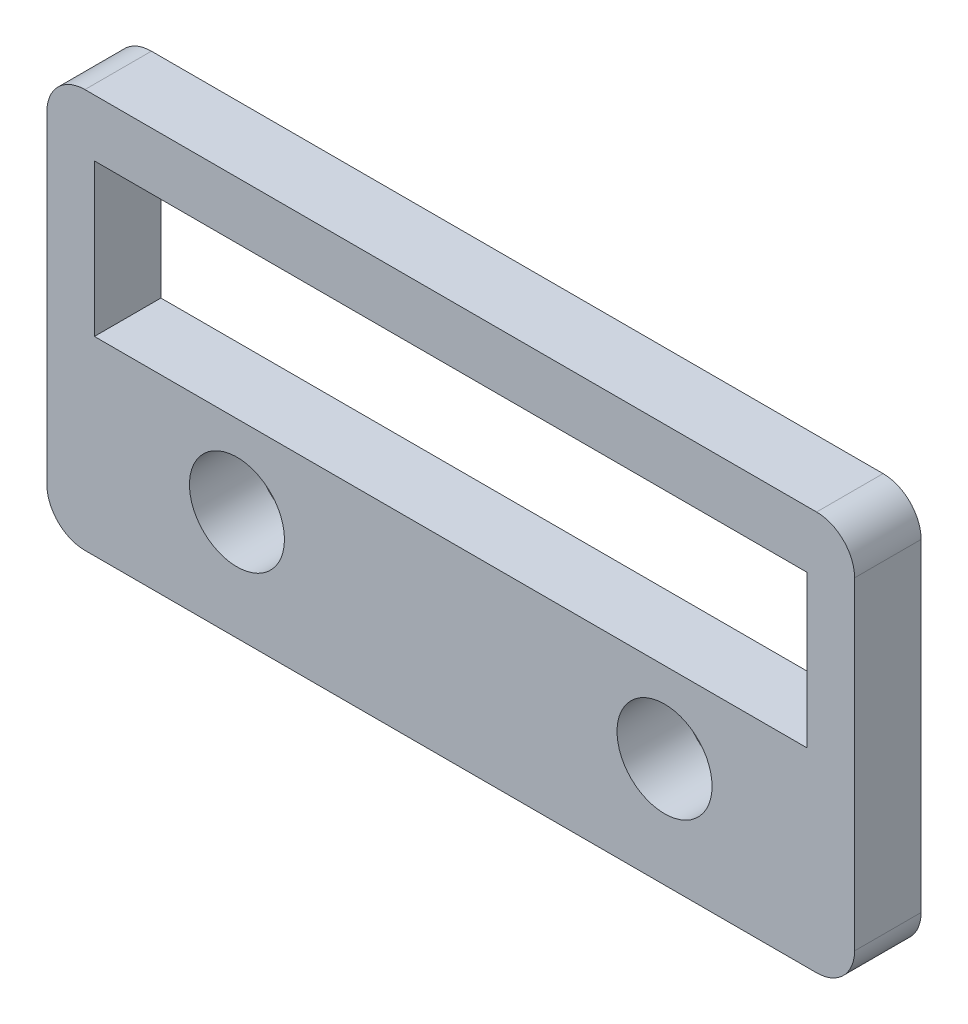
SolidWorks part; units mm, degrees
ref_plane "Front Plane" through (0, 0, 0) normal (0, 0, 1) x (1, 0, 0)
ref_plane "Top Plane" through (0, 0, 0) normal (0, 1, 0) x (1, 0, 0)
ref_plane "Right Plane" through (0, 0, 0) normal (1, 0, 0) x (0, 0, -1)
sketch "Sketch1" plane through (0, 0, 0) normal (0, 0, 1) x (1, 0, 0)
  line L1 (-29.3041, 27.5877) -> (47.6959, 27.5877)
  line L2 (-33.3041, 23.5877) -> (-33.3041, -10.4123)
  line L3 (-29.3041, -14.4123) -> (47.6959, -14.4123)
  line L4 (51.6959, 23.5877) -> (51.6959, -10.4123)
  arc A0 (47.6959, 27.5877) -> (51.6959, 23.5877) centre (47.6959, 23.5877) cw
  arc A1 (51.6959, -10.4123) -> (47.6959, -14.4123) centre (47.6959, -10.4123) cw
  arc A2 (-33.3041, -10.4123) -> (-29.3041, -14.4123) centre (-29.3041, -10.4123) ccw
  arc A3 (-33.3041, 23.5877) -> (-29.3041, 27.5877) centre (-29.3041, 23.5877) cw
  point P7 (51.6959, 27.5877)
  point P12 (-33.3041, -14.4123)
  point P15 (-33.3041, 27.5877)
  dimension "D4" = 4
  dimension "D1" = 85
  dimension "D2" = 42
  dimension "D3" = 33.3041
extrude "Boss-Extrude1" add sketch "Sketch1" along normal blind 7
sketch "Sketch2" plane through (0, 0, 7) normal (0, 0, 1) x (1, 0, 0)
  line L1 (-28.3041, 21.5877) -> (46.6959, 21.5877)
  line L2 (-28.3041, 21.5877) -> (-28.3041, 5.5877)
  line L3 (-28.3041, 5.5877) -> (46.6959, 5.5877)
  line L4 (46.6959, 21.5877) -> (46.6959, 5.5877)
  line L6 (47.6959, 27.5877) -> (-29.3041, 27.5877) construction
  line L7 (-33.3041, 23.5877) -> (-33.3041, -10.4123) construction
  dimension "D1" = 75
  dimension "D2" = 5
  dimension "D3" = 6
  dimension "D4" = 16
extrude "Cut-Extrude1" cut sketch "Sketch2" against normal blind 7
sketch "Sketch3" plane through (0, 0, 7) normal (0, 0, 1) x (1, 0, 0)
  line L0 (51.6959, -10.4123) -> (51.6959, 23.5877) construction
  line L1 (-29.3041, -14.4123) -> (47.6959, -14.4123) construction
  line L2 (-33.3041, 23.5877) -> (-33.3041, -10.4123) construction
  circle A0 centre (31.6959, -2.9123) radius 5
  circle A1 centre (-13.3041, -2.9123) radius 5
  dimension "D5" = 10
  dimension "D6" = 10
  dimension "D1" = 20
  dimension "D2" = 11.5
  dimension "D3" = 20
  dimension "D4" = 11.5
extrude "Cut-Extrude2" cut sketch "Sketch3" against normal blind 7
